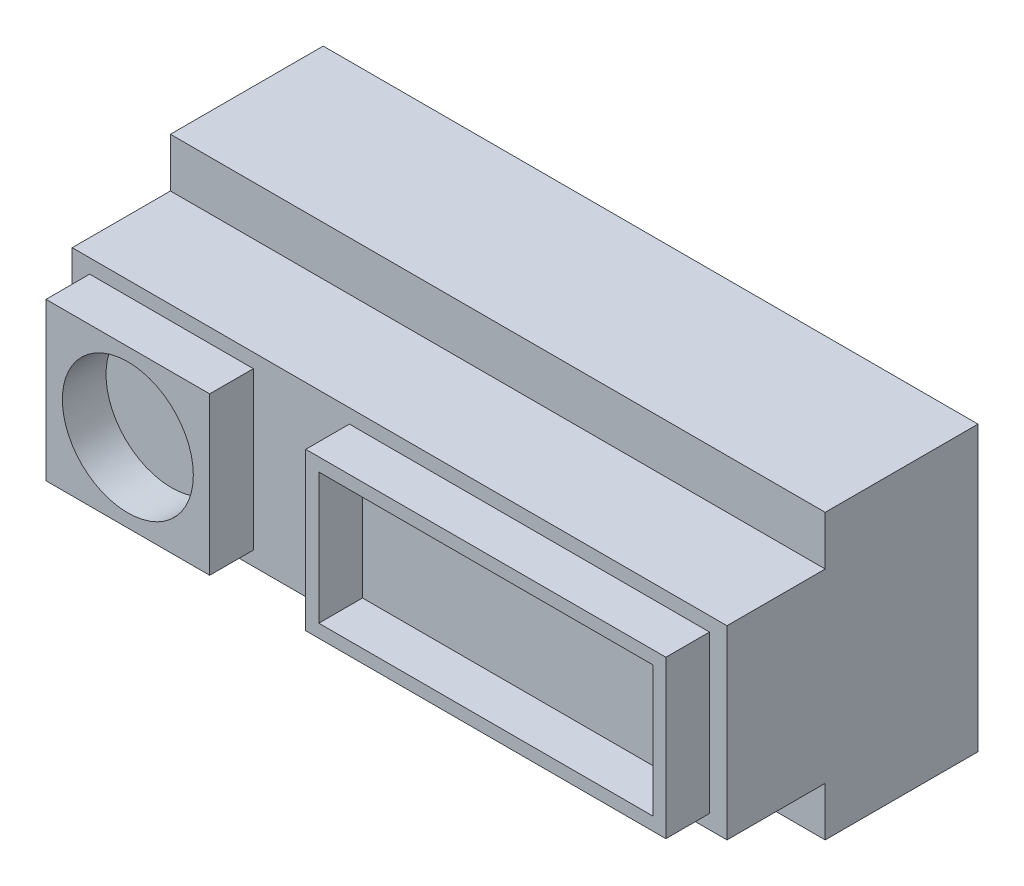
SolidWorks part; units mm, degrees
material "Плата обработки данных, простая"
ref_plane "Спереди" through (0, 0, 0) normal (0, 0, 1) x (1, 0, 0)
ref_plane "Сверху" through (0, 0, 0) normal (0, 1, 0) x (1, 0, 0)
ref_plane "Справа" through (0, 0, 0) normal (1, 0, 0) x (0, 0, -1)
sketch "Эскиз1" plane through (0, 0, 0) normal (0, 0, 1) x (1, 0, 0)
  line L0 (0, 0) -> (0, 64.0149) construction
  line L1 (-15, 0) -> (15, 0)
  line L2 (15, 13) -> (15, 0)
  line L3 (15, 13) -> (-15, 13)
  line L4 (-15, 13) -> (-15, 0)
  point P21 (0, 13)
  dimension "D1" = 30
  dimension "D2" = 13
extrude "Бобышка-Вытянуть1" add sketch "Эскиз1" along normal blind 1.4
sketch "Эскиз2" plane through (0, 0, 1.4) normal (0, 0, 1) x (1, 0, 0)
  line L1 (-15, 13) -> (15, 13)
  line L2 (-15, 13) -> (-15, 0)
  line L3 (-15, 0) -> (15, 0)
  line L4 (15, 13) -> (15, 0)
extrude "Бобышка-Вытянуть2" add sketch "Эскиз2" along normal blind 4
sketch "Эскиз3" plane through (0, 0, 5.4) normal (0, 0, 1) x (1, 0, 0)
  line L1 (-15, 13) -> (15, 13)
  line L2 (-15, 13) -> (-15, 0)
  line L3 (-15, 0) -> (15, 0)
  line L4 (15, 13) -> (15, 0)
extrude "Бобышка-Вытянуть3" add sketch "Эскиз3" along normal blind 1.6
sketch "Эскиз4" plane through (0, 0, 7) normal (0, 0, 1) x (1, 0, 0)
  line L0 (-15, 13) -> (-15, 0) construction
  line L1 (-15, 10.75) -> (15, 10.75)
  line L2 (-15, 10.75) -> (-15, 2.25)
  line L3 (-15, 2.25) -> (15, 2.25)
  line L4 (15, 10.75) -> (15, 2.25)
  line L7 (-15, 6.5) -> (18.75, 6.5) construction
  dimension "D1" = 8.5
  dimension "D2" = 4.25
extrude "Бобышка-Вытянуть4" add sketch "Эскиз4" along normal blind 4.5
sketch "Эскиз6" plane through (0, 0, 11.5) normal (0, 0, 1) x (1, 0, 0)
  line L0 (-15, 6.5) -> (31.9524, 6.5) construction
  line L1 (-2.3, 10.1) -> (14.2, 10.1)
  line L2 (-2.3, 10.1) -> (-2.3, 2.9)
  line L3 (-2.3, 2.9) -> (14.2, 2.9)
  line L4 (14.2, 10.1) -> (14.2, 2.9)
  line L5 (15, 2.25) -> (15, 10.75) construction
  line L6 (-6.7, 10.1) -> (-2.3, 10.1) construction
  line L7 (-14.2, 10.1) -> (-6.7, 10.1)
  line L8 (-14.2, 10.1) -> (-14.2, 2.9)
  line L9 (-14.2, 2.9) -> (-6.7, 2.9)
  line L10 (-6.7, 10.1) -> (-6.7, 2.9)
  line L11 (-1.7, 9.5) -> (13.6, 9.5)
  line L12 (13.6, 9.5) -> (13.6, 3.5)
  line L13 (-1.7, 3.5) -> (13.6, 3.5)
  line L14 (-1.7, 9.5) -> (-1.7, 3.5)
  line L15 (-15, 10.75) -> (-15, 2.25) construction
  line L16 (-6.7, 2.9) -> (-2.3, 2.9) construction
  circle A0 centre (-10.45, 6.5) radius 3
  dimension "D8" = 6
  dimension "D1" = 7.2
  dimension "D2" = 3.6
  dimension "D3" = 16.5
  dimension "D4" = 0.8
  dimension "D5" = 0.8
  dimension "D6" = 7.5
  dimension "D7" = 0.6
extrude "Бобышка-Вытянуть5" add sketch "Эскиз6" along normal blind 2
sketch "Эскиз7" plane through (0, 0, 7) normal (0, 0, 1) x (1, 0, 0)
  line L0 (-15, 0) -> (15, 0) construction
  line L2 (-5.25, -2.25) -> (5.25, -2.25)
  line L4 (-5.25, -2.25) -> (-5.25, 2.25)
  line L5 (-5.25, 2.25) -> (5.25, 2.25)
  line L6 (5.25, -2.25) -> (5.25, 2.25)
  line L7 (-5.25, -2.25) -> (5.25, 2.25) construction
  line L8 (-5.25, 2.25) -> (5.25, -2.25) construction
  line L9 (-15, 2.25) -> (15, 2.25) construction
  point P0 (0, 0)
  dimension "D1" = 10.5
extrude "Вырез-Вытянуть1" cut sketch "Эскиз7" against normal blind 12
sketch "Эскиз8" plane through (0, 2.25, 0) normal (0, -1, 0) x (1, 0, 0)
  line L0 (5.25, 0) -> (-5.25, 0) construction
  line L1 (-5, 3.6) -> (5, 3.6)
  line L2 (-5, 3.6) -> (-5, 2.5)
  line L3 (-5, 2.5) -> (5, 2.5)
  line L4 (5, 3.6) -> (5, 2.5)
  point P4 (0, 0)
  dimension "D1" = 10
  dimension "D2" = 5
  dimension "D3" = 1.1
  dimension "D4" = 2.5
extrude "Бобышка-Вытянуть6" add sketch "Эскиз8" along normal blind 8.05
